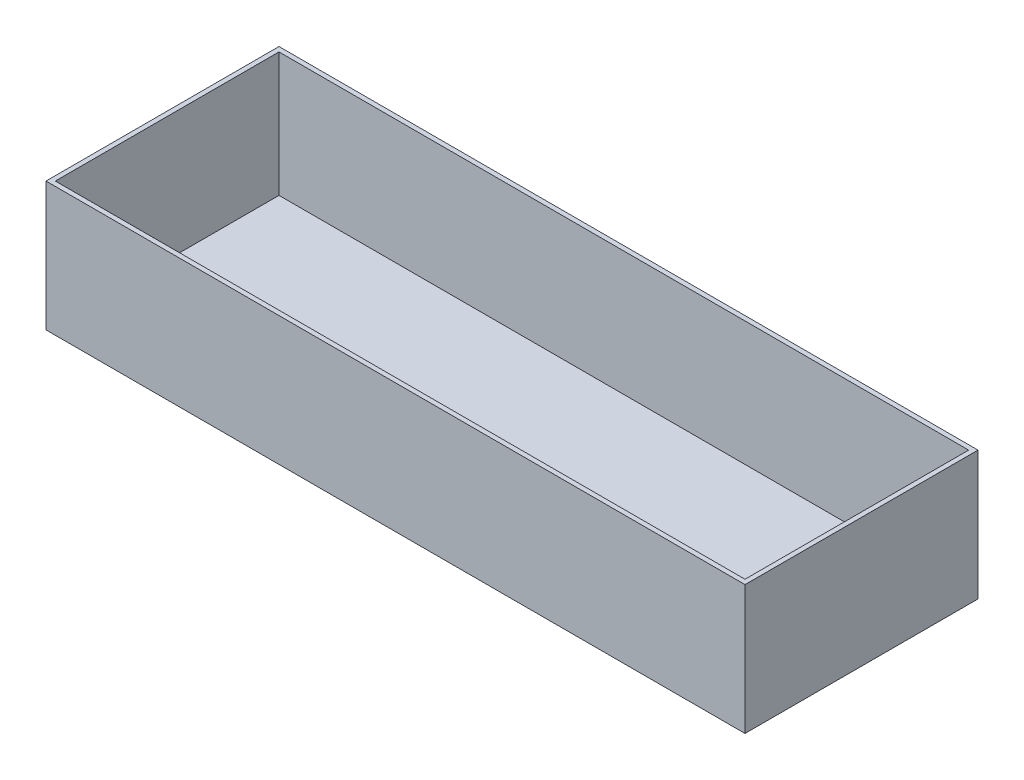
SolidWorks part; units mm, degrees
ref_plane "Front Plane" through (0, 0, 0) normal (0, 0, 1) x (1, 0, 0)
ref_plane "Top Plane" through (0, 0, 0) normal (0, 1, 0) x (1, 0, 0)
ref_plane "Right Plane" through (0, 0, 0) normal (1, 0, 0) x (0, 0, -1)
sketch "Sketch1" plane through (0, 0, 0) normal (0, 1, 0) x (1, 0, 0)
  line L1 (0, 0) -> (180, 0)
  line L2 (0, 0) -> (0, 60)
  line L3 (0, 60) -> (180, 60)
  line L4 (180, 0) -> (180, 60)
  dimension "D1" = 180
  dimension "D2" = 60
extrude "Boss-Extrude1" add sketch "Sketch1" along normal blind 1.2
sketch "Sketch3" plane through (0, 1.2, 0) normal (0, 1, 0) x (1, 0, 0)
  line L0 (1.2, 58.8) -> (1.2, 1.2)
  line L1 (0, 60) -> (180, 60)
  line L2 (0, 60) -> (0, 0)
  line L3 (0, 0) -> (180, 0)
  line L4 (180, 60) -> (180, 0)
  line L5 (1.2, 1.2) -> (178.8, 1.2)
  line L6 (178.8, 58.8) -> (178.8, 1.2)
  line L7 (1.2, 58.8) -> (178.8, 58.8)
  dimension "D1" = 1.2
extrude "Boss-Extrude2" add sketch "Sketch3" along normal blind 32
sketch "Sketch4" plane through (0, 1.2, 0) normal (0, 1, 0) x (1, 0, 0)
  line L0 (1.2, 58.8) -> (1.2, 1.2) construction
  line L1 (16.2, 8.3) -> (56.2, 8.3)
  line L2 (16.2, 8.3) -> (16.2, 7.5)
  line L3 (16.2, 7.5) -> (56.2, 7.5)
  line L4 (56.2, 8.3) -> (56.2, 7.5)
  line L5 (178.8, 58.8) -> (1.2, 58.8) construction
  dimension "D1" = 0.8
  dimension "D2" = 40
  dimension "D3" = 15
  dimension "D4" = 50.5
extrude "Boss-Extrude3" add sketch "Sketch4" along normal blind 10
